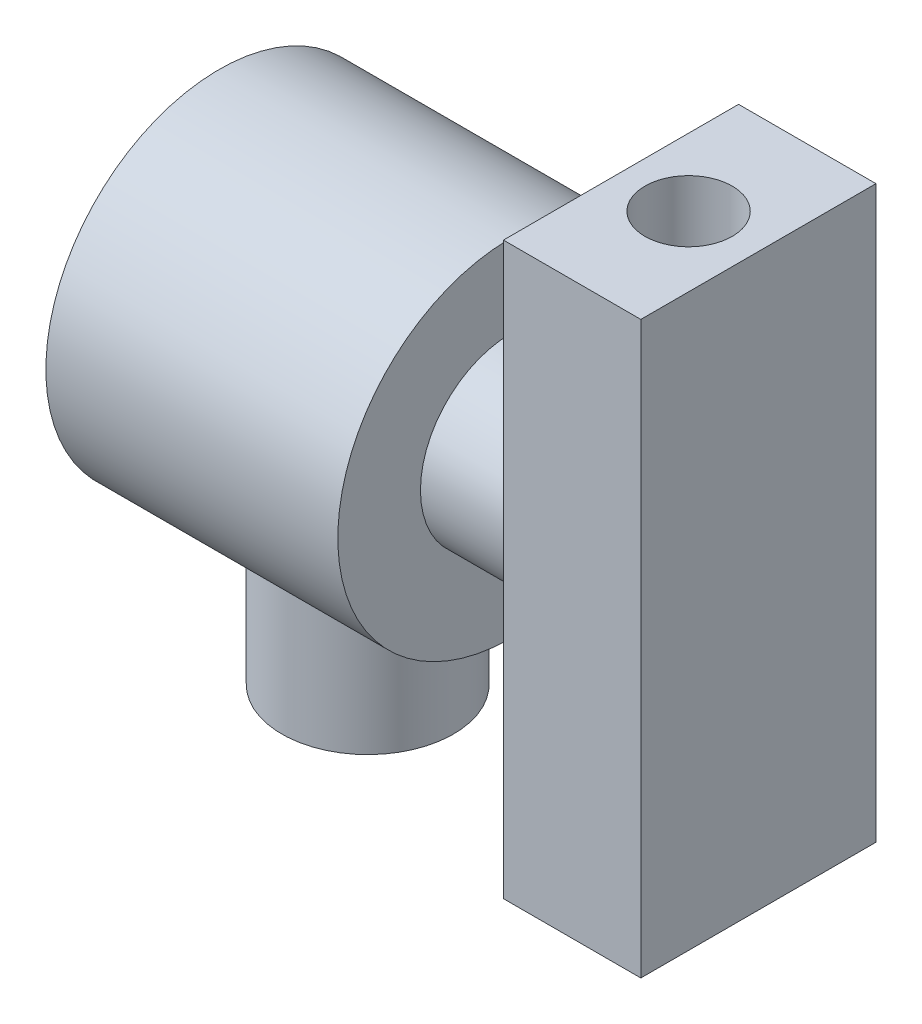
SolidWorks part; units mm, degrees
ref_plane "Front Plane" through (0, 0, 0) normal (0, 0, 1) x (1, 0, 0)
ref_plane "Top Plane" through (0, 0, 0) normal (0, 1, 0) x (1, 0, 0)
ref_plane "Right Plane" through (0, 0, 0) normal (1, 0, 0) x (0, 0, -1)
sketch "Sketch2" plane through (0, 0, 0) normal (1, 0, 0) x (0, 0, -1)
  circle A0 centre (0, 0) radius 25.225
  dimension "D1" = 50.45
extrude "Boss-Extrude1" add sketch "Sketch2" along normal blind 42.5
sketch "Sketch3" plane through (42.5, 0, 0) normal (1, 0, 0) x (0, 0, -1)
  circle A0 centre (0, 0) radius 13.1971
extrude "Boss-Extrude2" add sketch "Sketch3" along normal blind 16 separate body
sketch "Sketch4" plane through (58.5, 0, 0) normal (1, 0, 0) x (0, 0, -1)
  line L1 (17.115, 41.5155) -> (-17.115, 41.5155)
  line L2 (17.115, 41.5155) -> (17.115, -41.5155)
  line L3 (17.115, -41.5155) -> (-17.115, -41.5155)
  line L4 (-17.115, 41.5155) -> (-17.115, -41.5155)
  line L5 (17.115, 41.5155) -> (-17.115, -41.5155) construction
  line L6 (17.115, -41.5155) -> (-17.115, 41.5155) construction
  point P0 (0, 0)
extrude "Boss-Extrude3" add sketch "Sketch4" along normal blind 20 separate body
sketch "Sketch6" plane through (0, 41.5155, 0) normal (0, 1, 0) x (1, 0, 0)
  circle A0 centre (68.3393, 0) radius 6.35
  point P2 (68.3393, 0)
  dimension "D1" = 12.7
extrude "Cut-Extrude1" cut sketch "Sketch6" against normal blind 20
sketch "Sketch7" plane through (0, -41.5155, 0) normal (0, -1, 0) x (1, 0, 0)
  circle A0 centre (68.4753, 0) radius 6.35
  point P2 (68.4753, 0)
  dimension "D1" = 12.7
extrude "Cut-Extrude2" cut sketch "Sketch7" against normal blind 20
sketch "Sketch8" plane through (0, -41.5155, 0) normal (0, -1, 0) x (1, 0, 0)
  circle A0 centre (21.62, 0) radius 12.5
  point P2 (20.5767, 0)
  point P3 (0, 0)
  point P4 (0, 0)
  point P5 (20.6636, 0)
  point P6 (22.4894, 0)
  point P7 (21.4461, 0)
  point P8 (21.62, 0)
  dimension "D1" = 25
extrude "Boss-Extrude4" add sketch "Sketch8" against normal blind 19
